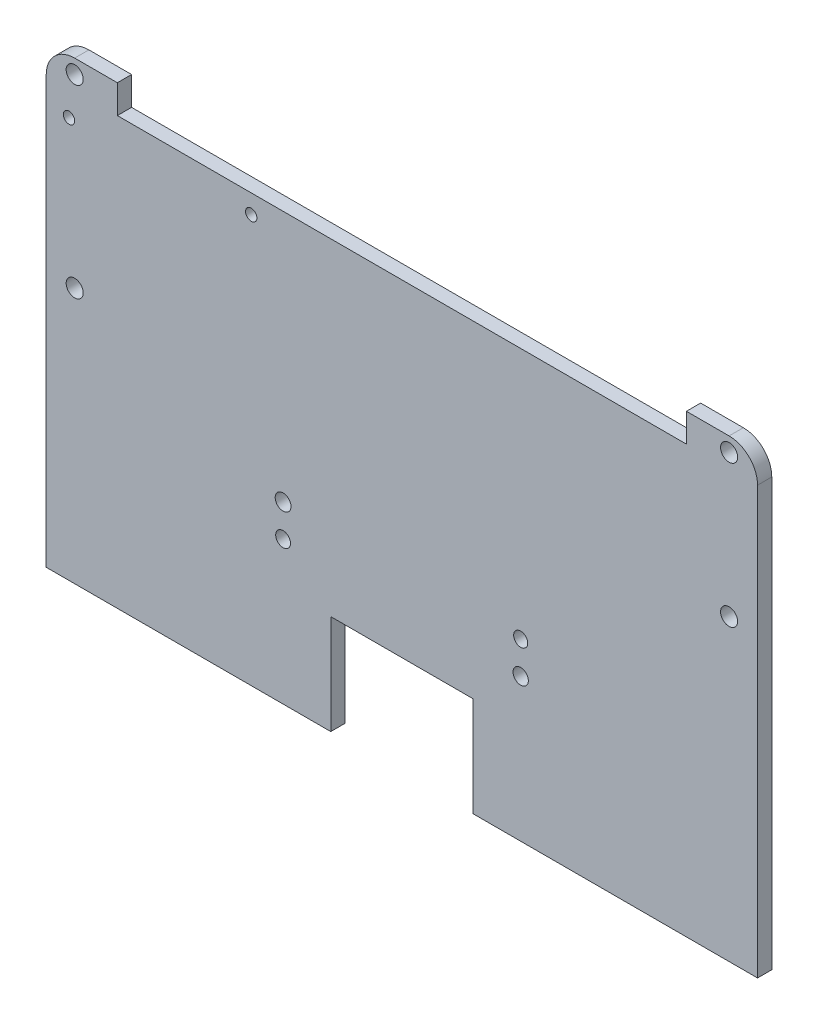
SolidWorks part; units mm, degrees
material "Teck"
ref_plane "Plan de face" through (0, 0, 0) normal (0, 0, 1) x (1, 0, 0)
ref_plane "Plan de dessus" through (0, 0, 0) normal (0, 1, 0) x (1, 0, 0)
ref_plane "Plan de droite" through (0, 0, 0) normal (1, 0, 0) x (0, 0, -1)
sketch "Esquisse1" plane through (0, 0, 0) normal (0, 0, 1) x (1, 0, 0)
  line L1 (10, 0) -> (240, 0)
  line L2 (0, -10) -> (0, -160)
  line L3 (0, -160) -> (250, -160)
  line L4 (250, -10) -> (250, -160)
  arc A0 (240, 0) -> (250, -10) centre (240, -10) cw
  arc A1 (10, 0) -> (0, -10) centre (10, -10) ccw
  point P7 (250, 0)
  point P10 (0, 0)
  dimension "D3" = 10
  dimension "D1" = 250
  dimension "D2" = 160
extrude "Boss.-Extru.1" add sketch "Esquisse1" along normal blind 5
sketch "Esquisse2" plane through (0, 0, 5) normal (0, 0, 1) x (1, 0, 0)
  line L0 (240, 0) -> (10, 0) construction
  line L1 (0, -10) -> (0, -160) construction
  line L2 (125, 0) -> (125, -160) construction
  line L3 (0, -160) -> (250, -160) construction
  line L4 (0, -10) -> (0, -160) construction
  line L5 (250, -160) -> (250, -10) construction
  circle A0 centre (10, -5) radius 3
  circle A4 centre (240, -55) radius 3
  circle A5 centre (240, -5) radius 3
  circle A6 centre (10, -70) radius 3
  dimension "D1" = 6
  dimension "D2" = 50
  dimension "D6" = 10
  dimension "D5" = 6
  dimension "D9" = 6
  dimension "D3" = 5
  dimension "D4" = 10
  dimension "D7" = 65
  dimension "D8" = 10
extrude "Enlèv. mat.-Extru.1" cut sketch "Esquisse2" against normal blind 5
sketch "Esquisse3" plane through (0, 0, 0) normal (0, 0, -1) x (-1, 0, 0)
  line L0 (-25, 0) -> (-225, 0)
  line L1 (0, -160) -> (-250, -160) construction
  line L2 (-225, 0) -> (-225, -10)
  line L3 (-225, -10) -> (-25, -10)
  line L4 (-25, -10) -> (-25, 0)
  line L7 (-240, 0) -> (-10, 0) construction
  point P4 (-125, 0)
  point P11 (-125, -160)
  dimension "D1" = 200
  dimension "D2" = 10
extrude "Enlèv. mat.-Extru.2" cut sketch "Esquisse3" against normal blind 10
sketch "Esquisse4" plane through (0, 0, 0) normal (0, 0, -1) x (-1, 0, 0)
  line L0 (-6, -21.6323) -> (-6, -16.6323) construction
  circle A0 centre (-8.0026, -19.1323) radius 2
  circle A1 centre (-72.0478, -16.6499) radius 2
  point P6 (-6, -19.1323)
  dimension "D1" = 4
  dimension "D2" = 0
extrude "Enlèv. mat.-Extru.3" cut sketch "Esquisse4" against normal through all
sketch "Esquisse5" plane through (0, 0, 0) normal (0, 0, -1) x (-1, 0, 0)
  line L0 (-125, -10) -> (-125, -160) construction
  line L1 (-225, -10) -> (-25, -10) construction
  line L2 (0, -160) -> (-250, -160) construction
  line L3 (-100, -160) -> (-100, -125)
  line L4 (-100, -125) -> (-150, -125)
  line L5 (-150, -125) -> (-150, -160)
  line L6 (-150, -160) -> (-100, -160)
  point P11 (-125, -125)
  dimension "D1" = 35
  dimension "D2" = 50
extrude "Enlèv. mat.-Extru.4" cut sketch "Esquisse5" against normal through all
sketch "Esquisse6" plane through (0, 0, 5) normal (0, 0, 1) x (1, 0, 0)
  circle A0 centre (83.25, -109.8) radius 2.6
  circle A1 centre (83.25, -98.5) radius 2.7793
  circle A2 centre (166.75, -109.8) radius 2.6976
  circle A3 centre (166.75, -98.5) radius 2.4693
extrude "Enlèv. mat.-Extru.5" cut sketch "Esquisse6" against normal through all
